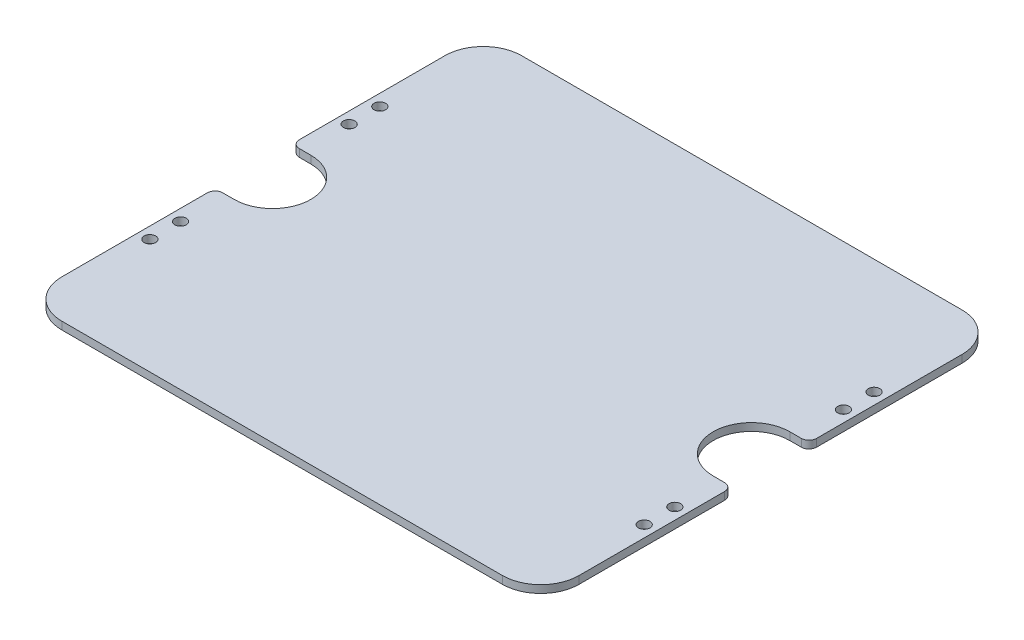
SolidWorks part; units mm, degrees
ref_plane "前视基准面" through (0, 0, 0) normal (0, 0, 1) x (1, 0, 0)
ref_plane "上视基准面" through (0, 0, 0) normal (0, 1, 0) x (1, 0, 0)
ref_plane "右视基准面" through (0, 0, 0) normal (1, 0, 0) x (0, 0, -1)
sketch "草图1" plane through (0, 0, 0) normal (0, 1, 0) x (1, 0, 0)
  line L0 (-65.5, 10) -> (-62.5, 10)
  line L1 (-57.5, 60) -> (57.5, 60)
  line L2 (-67.5, 50) -> (-67.5, 12)
  line L3 (-57.5, -60) -> (57.5, -60)
  line L4 (67.5, 50) -> (67.5, 12)
  line L5 (-67.5, 60) -> (67.5, -60) construction
  line L6 (-67.5, -60) -> (67.5, 60) construction
  line L7 (-65.5, -10) -> (-62.5, -10)
  line L8 (0, 0) -> (0, 91.5573) construction
  line L9 (0, 0) -> (-115.8836, 0) construction
  line L10 (-67.5, -12) -> (-67.5, -50)
  line L11 (65.5, -10) -> (62.5, -10)
  line L12 (65.5, 10) -> (62.5, 10)
  line L13 (67.5, -12) -> (67.5, -50)
  circle A0 centre (-64.5, 30) radius 1.5
  circle A1 centre (64.5, 30) radius 1.5
  circle A2 centre (64.5, -30) radius 1.5
  circle A3 centre (-64.5, -30) radius 1.5
  circle A4 centre (-64.5, 30) radius 3 construction
  circle A5 centre (64.5, 30) radius 3 construction
  circle A6 centre (64.5, -30) radius 3 construction
  circle A7 centre (-64.5, -30) radius 3 construction
  arc A8 (-62.5, 10) -> (-62.5, -10) centre (-62.5, 0) cw
  arc A9 (62.5, 10) -> (62.5, -10) centre (62.5, 0) ccw
  circle A10 centre (-64.5, 22) radius 1.5
  circle A11 centre (64.5, 22) radius 1.5
  circle A12 centre (64.5, -22) radius 1.5
  circle A13 centre (-64.5, -22) radius 1.5
  arc A14 (67.5, -12) -> (65.5, -10) centre (65.5, -12) ccw
  arc A15 (67.5, 12) -> (65.5, 10) centre (65.5, 12) cw
  arc A16 (-67.5, -12) -> (-65.5, -10) centre (-65.5, -12) cw
  arc A17 (-65.5, 10) -> (-67.5, 12) centre (-65.5, 12) cw
  arc A18 (-67.5, 50) -> (-57.5, 60) centre (-57.5, 50) cw
  arc A19 (-57.5, -60) -> (-67.5, -50) centre (-57.5, -50) cw
  arc A20 (57.5, -60) -> (67.5, -50) centre (57.5, -50) ccw
  arc A21 (67.5, 50) -> (57.5, 60) centre (57.5, 50) ccw
  point P0 (0, 0)
  point P42 (67.5, -10)
  point P45 (67.5, 10)
  point P48 (-67.5, -10)
  point P51 (-67.5, 10)
  dimension "D1" = 3
  dimension "D6" = 6
  dimension "D7" = 6
  dimension "D8" = 6
  dimension "D9" = 6
  dimension "D15" = 3
  dimension "D17" = 2
  dimension "D18" = 10
  dimension "D19" = 10
  dimension "D2" = 129
  dimension "D3" = 60
  dimension "D4" = 30
  dimension "D5" = 64.5
  dimension "D10" = 120
  dimension "D11" = 135
  dimension "D12" = 20
  dimension "D13" = 10
  dimension "D14" = 5
  dimension "D16" = 22
extrude "凸台-拉伸1" add sketch "草图1" along normal blind 2
